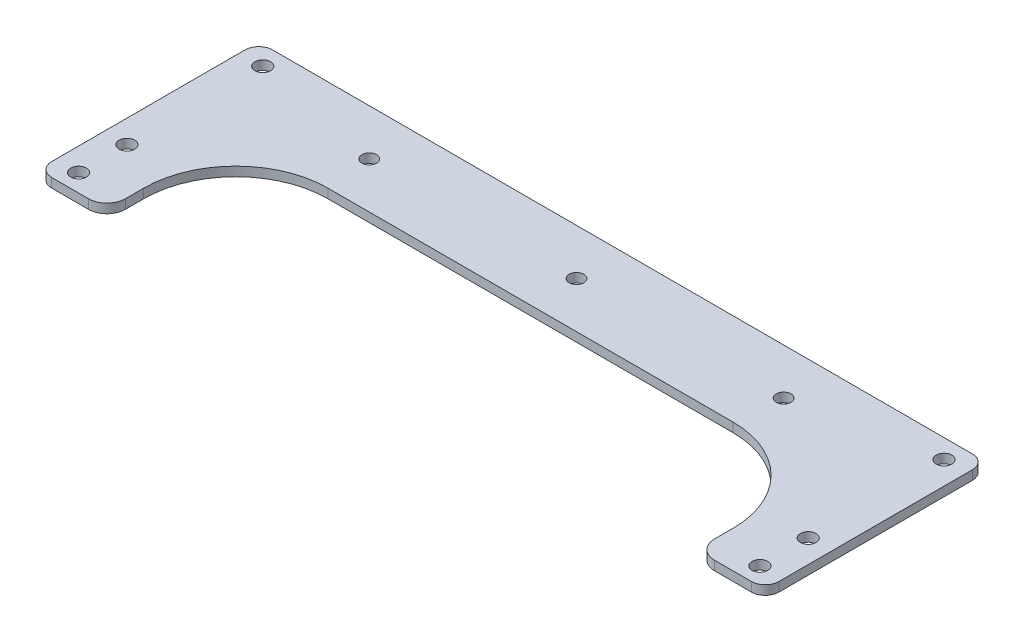
SolidWorks part; units mm, degrees
ref_plane "前视基准面" through (0, 0, 0) normal (0, 0, 1) x (1, 0, 0)
ref_plane "上视基准面" through (0, 0, 0) normal (0, 1, 0) x (1, 0, 0)
ref_plane "右视基准面" through (0, 0, 0) normal (1, 0, 0) x (0, 0, -1)
other "Configuration Table"
sketch "草图1" plane through (0, 0, 0) normal (0, 1, 0) x (1, 0, 0)
  line L1 (-79, -24) -> (79, -24)
  line L2 (-79, -24) -> (-79, 24)
  line L3 (-79, 24) -> (79, 24)
  line L4 (79, -24) -> (79, 24)
  line L5 (-79, -24) -> (79, 24) construction
  line L6 (-79, 24) -> (79, -24) construction
  point P0 (0, 0)
extrude "凸台-拉伸1" add sketch "草图1" along normal blind 2
sketch "草图2" plane through (0, 2, 0) normal (0, 1, 0) x (1, 0, 0)
  line L0 (-79, -24) -> (-64, -24)
  line L1 (-79, -24) -> (79, -24) construction
  line L2 (79, -24) -> (64, -24)
  line L3 (-64, -24) -> (-64, 4)
  line L4 (64, -24) -> (64, 4)
  line L5 (64, 4) -> (-64, 4)
  line L6 (-64, -24) -> (64, -24)
  line M4 (-79, -24) -> (79, -24)
extrude "切除-拉伸1" cut sketch "草图2" against normal blind 2 contours L4 L5 L3 M4
sketch "草图4" plane through (0, 2, 0) normal (0, 1, 0) x (1, 0, 0)
  line L0 (0, 19.85) -> (0, 11.6752) construction
  line L2 (-74, 19.85) -> (74, 19.85) construction
  circle A0 centre (-74, 19.85) radius 1.7
  circle A1 centre (-74, -9.65) radius 1.7
  circle A2 centre (-74, -20.15) radius 1.7
  circle A3 centre (74, -20.15) radius 1.7
  circle A4 centre (74, -9.65) radius 1.7
  circle A5 centre (74, 19.85) radius 1.7
  point P7 (0, 19.85)
extrude "切除-拉伸2" cut sketch "草图4" against normal blind 2
sketch "草图5" plane through (0, 2, 0) normal (0, 1, 0) x (1, 0, 0)
  circle A0 centre (0, 14) radius 1.6
  circle A1 centre (-45, 14) radius 1.6
  circle A2 centre (45, 14) radius 1.6
extrude "切除-拉伸3" cut sketch "草图5" against normal blind 2
fillet "圆角4" radius 3 4 edges at (79, 1, -24) (79, 1, 24) (-79, 1, -24) (-79, 1, 24)
fillet "圆角5" radius 4 2 edges at (64, 1, 24) (-64, 1, 24)
fillet "圆角6" radius 20 2 edges at (-64, 1, -4) (64, 1, -4)
